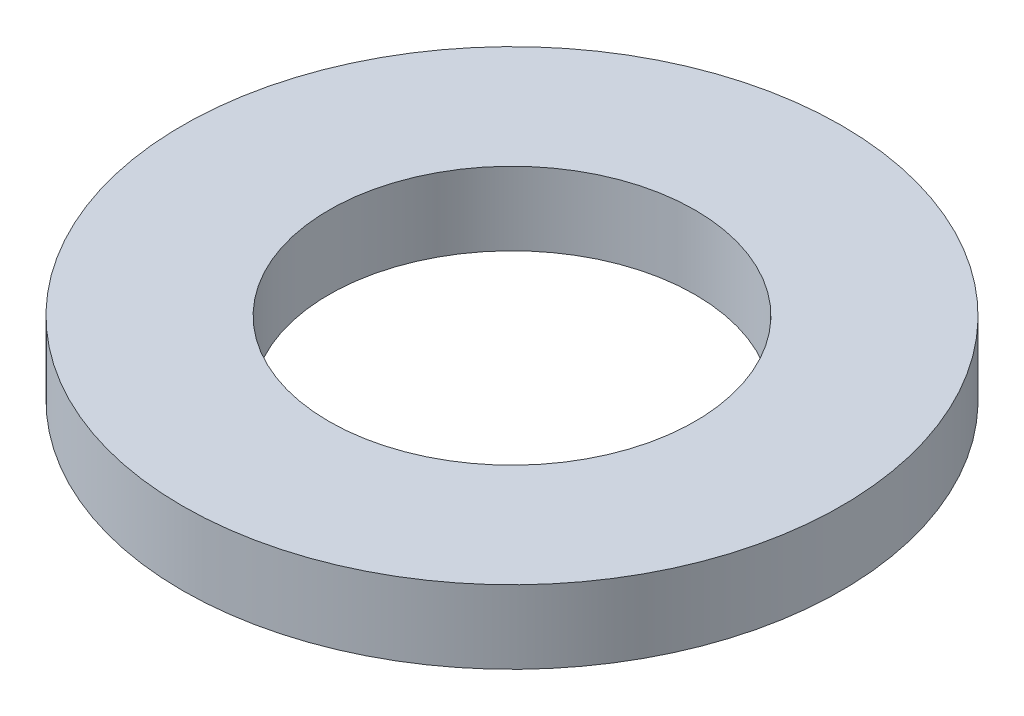
SolidWorks part; units mm, degrees
ref_plane "Front Plane" through (0, 0, 0) normal (0, 0, 1) x (1, 0, 0)
ref_plane "Top Plane" through (0, 0, 0) normal (0, 1, 0) x (1, 0, 0)
ref_plane "Right Plane" through (0, 0, 0) normal (1, 0, 0) x (0, 0, -1)
sketch "Sketch1" plane through (0, 0, 0) normal (0, 1, 0) x (1, 0, 0)
  circle A4 centre (12.8686, -5) radius 4.5
  circle A5 centre (12.8686, -5) radius 2.5
  dimension "D5" = 9
  dimension "D6" = 5
extrude "Boss-Extrude1" add sketch "Sketch1" along normal blind 1
